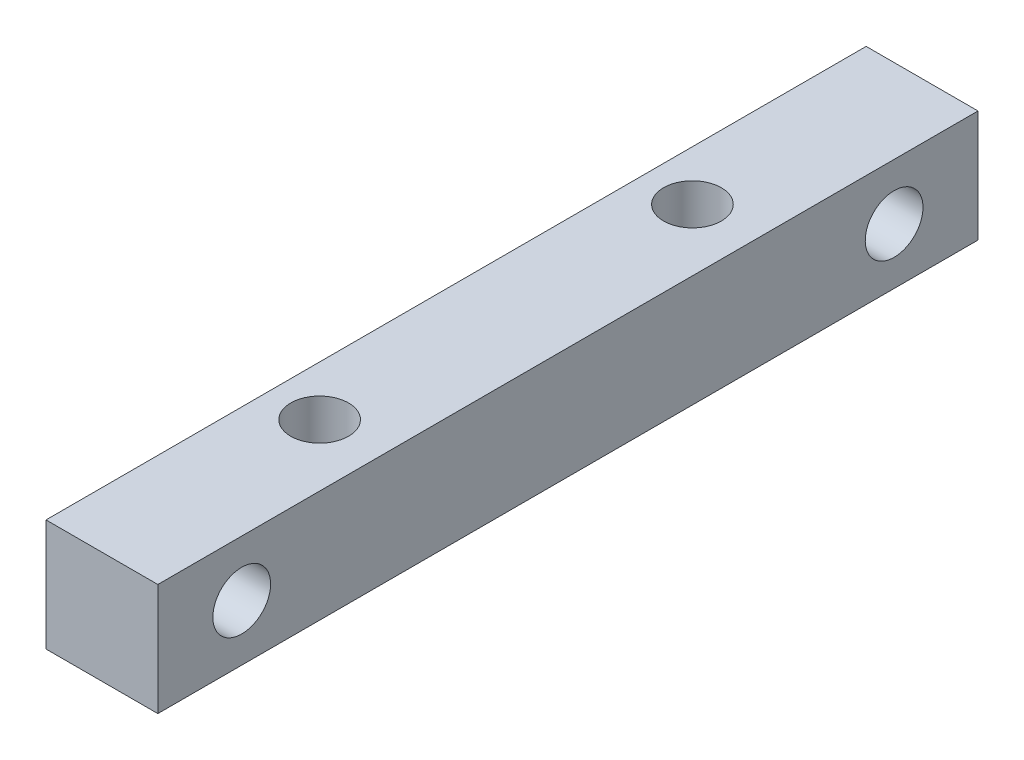
SolidWorks part; units mm, degrees
material "6061 合金"
ref_plane "前视基准面" through (0, 0, 0) normal (0, 0, 1) x (1, 0, 0)
ref_plane "上视基准面" through (0, 0, 0) normal (0, 1, 0) x (1, 0, 0)
ref_plane "右视基准面" through (0, 0, 0) normal (1, 0, 0) x (0, 0, -1)
other "Configuration Table"
sketch "草图1" plane through (0, 0, 0) normal (0, 0, 1) x (1, 0, 0)
  line L1 (-3, 3) -> (3, 3)
  line L2 (-3, 3) -> (-3, -3)
  line L3 (-3, -3) -> (3, -3)
  line L4 (3, 3) -> (3, -3)
  line L5 (-3, 3) -> (3, -3) construction
  line L6 (-3, -3) -> (3, 3) construction
  point P0 (0, 0)
  dimension "D1" = 6
  dimension "D2" = 6
extrude "凸台-拉伸1" add sketch "草图1" along normal mid plane 44
sketch "草图3" plane through (3, 0, 0) normal (1, 0, 0) x (0, 0, -1)
  line L0 (17.5, 0) -> (-17.5, 0) construction
  circle A0 centre (-17.5, 0) radius 1.55
  circle A1 centre (17.5, 0) radius 1.55
  point P4 (0, 0)
  dimension "D2" = 3.1
  dimension "D1" = 35
extrude "切除-拉伸1" cut sketch "草图3" against normal blind 44
sketch "草图6" plane through (0, 3, 0) normal (0, 1, 0) x (1, 0, 0)
  line L0 (-0.3205, 10) -> (-0.3205, -10) construction
  circle A0 centre (-0.3205, -10) radius 1.55
  circle A1 centre (-0.3205, 10) radius 1.55
  point P5 (-0.3205, 0)
  dimension "D1" = 3.1
extrude "切除-拉伸2" cut sketch "草图6" against normal blind 10
